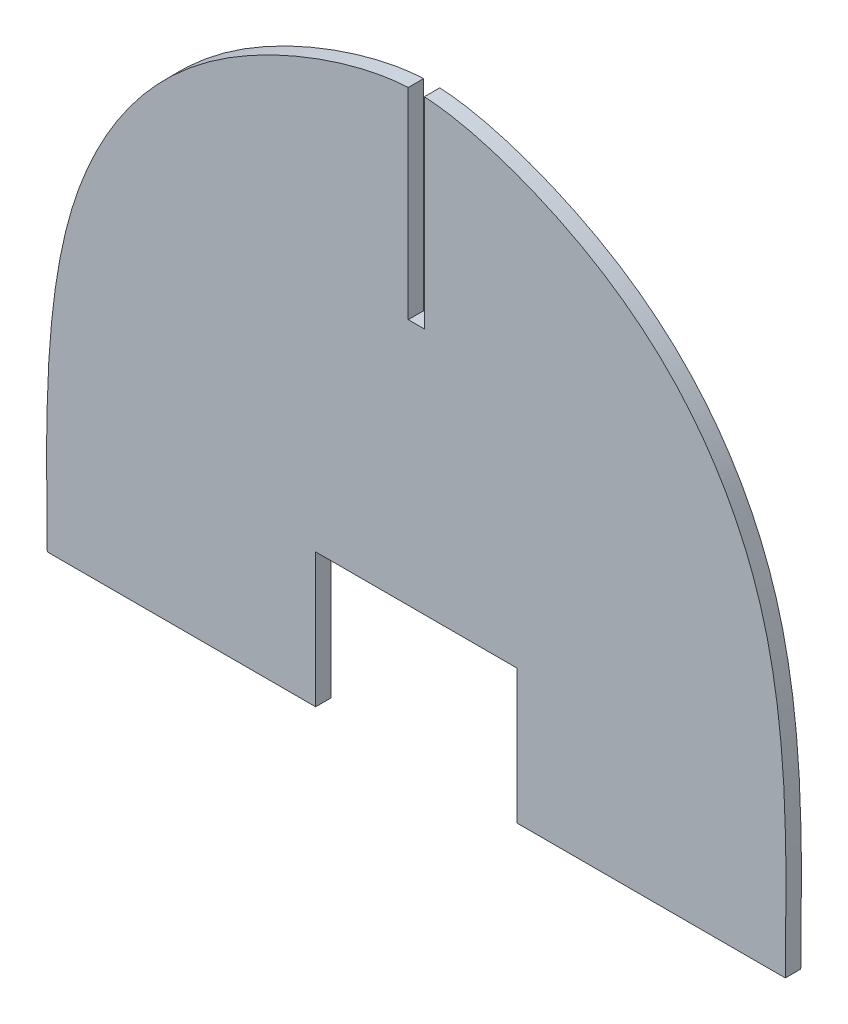
SolidWorks part; units mm, degrees
ref_plane "Front" through (0, 0, 0) normal (0, 0, 1) x (1, 0, 0)
ref_plane "Top" through (0, 0, 0) normal (0, 1, 0) x (1, 0, 0)
ref_plane "Right" through (0, 0, 0) normal (1, 0, 0) x (0, 0, -1)
sketch "Sketch1" plane through (0, 0, 0) normal (0, 0, 1) x (1, 0, 0)
  line L0 (0, 260.35) -> (65.904, 260.35) construction
  line L1 (139.7, 39.6875) -> (139.7, 168.303) construction
  spline S0 degree 3 poles (0, 260.35) (16.0709, 260.35) (56.7758, 247.6395) (104.3034, 213.3368) (143.6282, 143.2438) (139.7, 69.95) (139.7, 39.6875) knots 0 0 0 0 0.196513 0.377405 0.603721 1 1 1 1
sketch "Sketch2" plane through (0, 0, 0) normal (0, 0, 1) x (1, 0, 0)
  line L0 (0, 260.35) -> (0, 39.6875)
  line L1 (0, 39.6875) -> (139.7, 39.6875)
  spline S0 degree 3 poles (3173.9016, -2155.9728) (-425.3629, 237.3043) (-51.2681, 325.6195) (104.3034, 213.3368) (237.4874, -24.0519) (-210.8777, -561.6611) (2178.1983, 3480.679) knots -1.372433 -1.372433 -1.372433 -1.372433 0.196513 0.377405 0.603721 2.917734 2.917734 2.917734 2.917734 only from (0, 260.35) to (139.7, 39.6875) construction
  spline S1 degree 3 poles (0, 260.35) (16.0709, 260.35) (56.7758, 247.6395) (104.3034, 213.3368) (143.6282, 143.2438) (139.7, 69.95) (139.7, 39.6875) knots 0 0 0 0 0.196513 0.377405 0.603721 1 1 1 1
extrude "Boss-Extrude1" add sketch "Sketch2" along normal blind 5.842
sketch "Sketch3" plane through (0, 0, 5.842) normal (0, 0, 1) x (1, 0, 0)
  line L1 (0, 39.6875) -> (38.1, 39.6875)
  line L2 (0, 39.6875) -> (0, 90.4875)
  line L3 (0, 90.4875) -> (38.1, 90.4875)
  line L4 (38.1, 39.6875) -> (38.1, 90.4875)
  line L5 (0, 260.35) -> (3.048, 260.35)
  line L6 (0, 260.35) -> (0, 184.15)
  line L7 (0, 184.15) -> (3.048, 184.15)
  line L8 (3.048, 260.35) -> (3.048, 184.15)
  dimension "D1" = 38.1
  dimension "D2" = 50.8
  dimension "D3" = 76.2
  dimension "D4" = 3.048
extrude "Cut-Extrude1" cut sketch "Sketch3" against normal through all contours L3 L4 L1 L2 | L8 L7 L6 L5
mirror "Mirror1" about plane through (0, 0, 0) normal (1, 0, 0) of bodies 102
